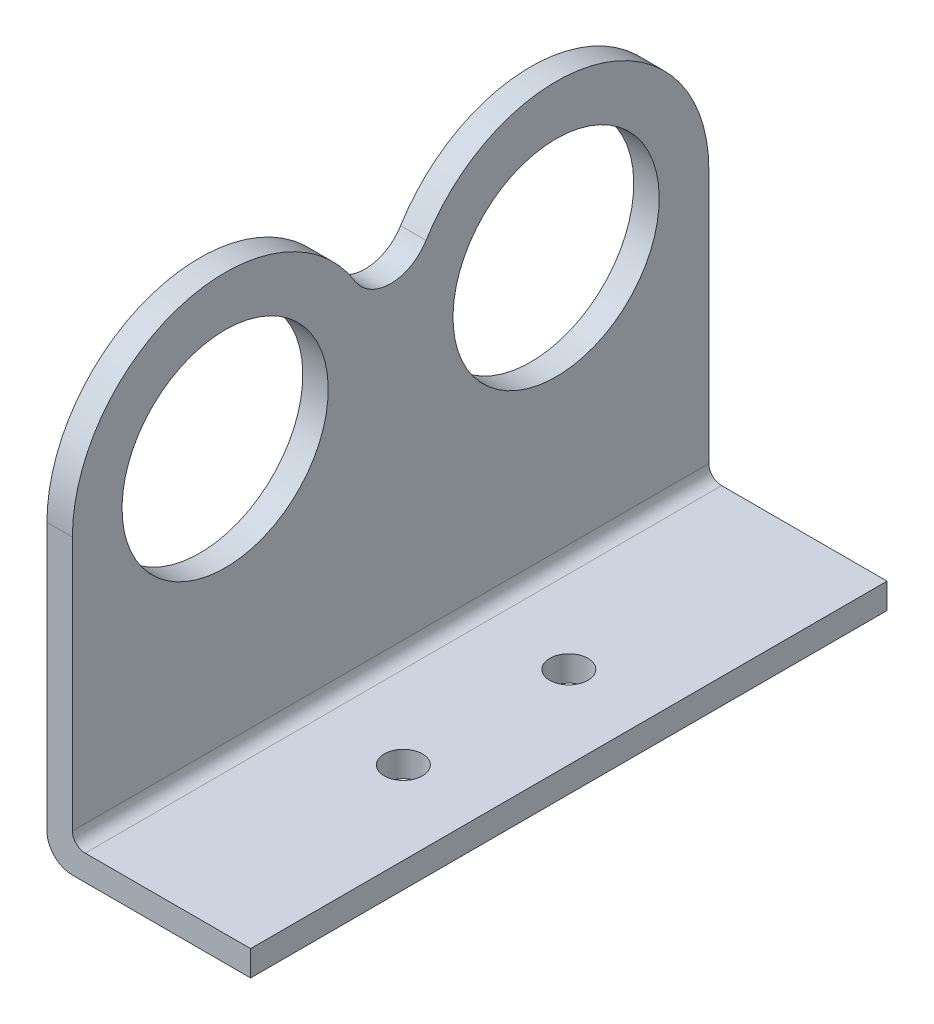
SolidWorks part; units mm, degrees
material "Acrylic (Medium-high impact)"
ref_plane "Front Plane" through (0, 0, 0) normal (0, 0, 1) x (1, 0, 0)
ref_plane "Top Plane" through (0, 0, 0) normal (0, 1, 0) x (1, 0, 0)
ref_plane "Right Plane" through (0, 0, 0) normal (1, 0, 0) x (0, 0, -1)
sketch "Sketch1" plane through (0, 0, 0) normal (0, 0, 1) x (1, 0, 0)
  line L0 (0, 35) -> (0, 2)
  line L1 (2, 0) -> (16, 0)
  line L2 (16, 0) -> (16, 2)
  line L3 (16, 2) -> (3, 2)
  line L4 (2, 3) -> (2, 35)
  line L5 (2, 35) -> (0, 35)
  arc A0 (0, 2) -> (2, 0) centre (2, 2) ccw
  arc A1 (2, 3) -> (3, 2) centre (3, 3) ccw
  point P9 (0, 0)
  dimension "D5" = 2
  dimension "D6" = 1
  dimension "D1" = 2
  dimension "D2" = 2
  dimension "D3" = 35
  dimension "D4" = 16
extrude "Boss-Extrude1" add sketch "Sketch1" along normal blind 50
sketch "Sketch2" plane through (0, 2, 0) normal (0, 1, 0) x (1, 0, 0)
  line L0 (16, -50) -> (3, -50) construction
  line L1 (16, -50) -> (16, 0) construction
  circle A0 centre (9.5, -18.5) radius 1.5
  circle A1 centre (9.5, -31.5) radius 1.5
  dimension "D1" = 3
  dimension "D2" = 3
  dimension "D3" = 13
  dimension "D4" = 18.5
  dimension "D5" = 6.5
  dimension "D6" = 18.5
extrude "Cut-Extrude1" cut sketch "Sketch2" against normal blind 50
sketch "Sketch3" plane through (2, 0, 0) normal (1, 0, 0) x (0, 0, -1)
  line L0 (-12, 35) -> (0, 35)
  line L1 (-50, 35) -> (0, 35) construction
  line L2 (0, 3) -> (0, 35) construction
  line L3 (-50, 3) -> (-50, 35) construction
  line L4 (-38, 35) -> (-50, 35)
  line L5 (-50, 35) -> (-50, 23)
  line L6 (0, 35) -> (0, 23)
  line L7 (-38, 35) -> (-12, 35)
  line L8 (-50, 0) -> (0, 0) construction
  circle A0 centre (-38, 23) radius 8.1
  circle A1 centre (-12, 23) radius 8.1
  arc A2 (-27.7801, 29.2892) -> (-50, 23) centre (-38, 23) ccw
  arc A3 (0, 23) -> (-22.2199, 29.2892) centre (-12, 23) ccw
  arc A4 (-27.7801, 29.2892) -> (-22.2199, 29.2892) centre (-25, 31) ccw
  line M7 (0, 3) -> (0, 35)
  line M8 (0, 35) -> (-50, 35)
  line M9 (-50, 35) -> (-50, 3)
  dimension "D2" = 16.2
  dimension "D3" = 16.2
  dimension "D1" = 26
  dimension "D4" = 4
  dimension "D5" = 23
  dimension "D6" = 25
extrude "Cut-Extrude2" cut sketch "Sketch3" against normal blind 50 contours A1 | A0 | A2 M8 M9 | A2 A4 A3 M8 | A3 M7 M8
